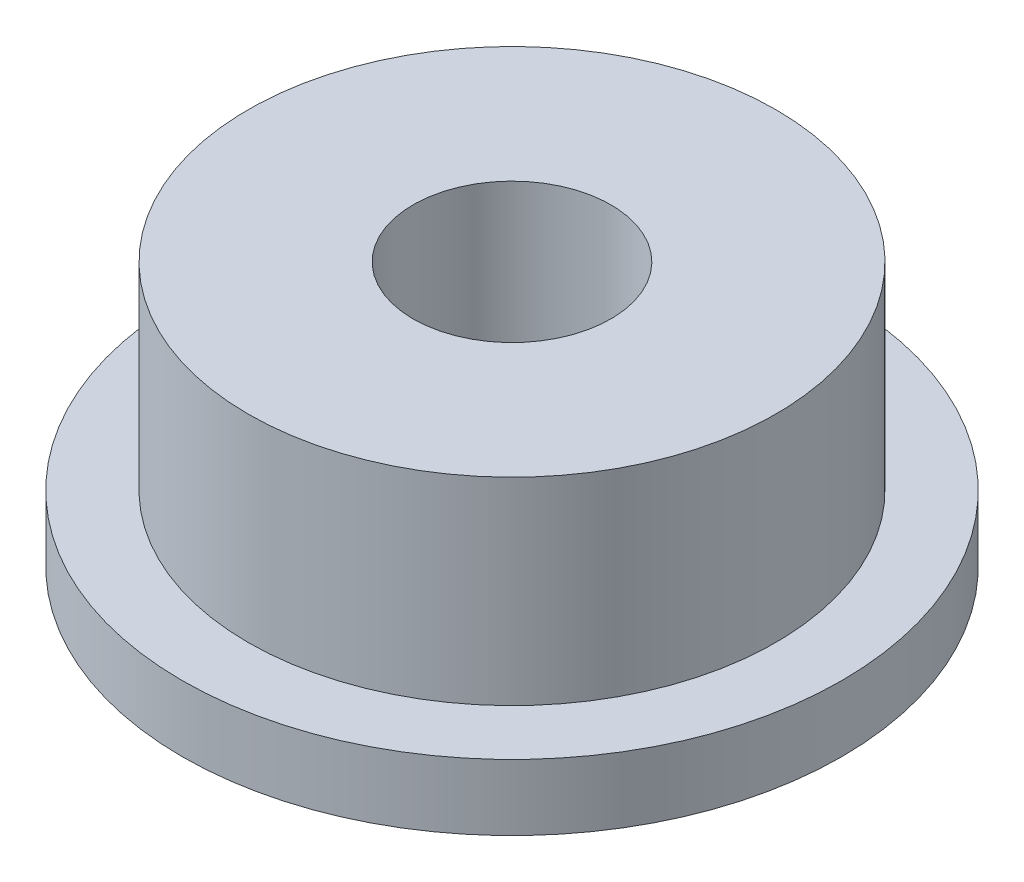
SolidWorks part; units mm, degrees
ref_plane "前视基准面" through (0, 0, 0) normal (0, 0, 1) x (1, 0, 0)
ref_plane "上视基准面" through (0, 0, 0) normal (0, 1, 0) x (1, 0, 0)
ref_plane "右视基准面" through (0, 0, 0) normal (1, 0, 0) x (0, 0, -1)
sketch "草图1" plane through (0, 0, 0) normal (0, 1, 0) x (1, 0, 0)
  circle A0 centre (0, 0) radius 5
  circle A1 centre (0, 0) radius 1.5
  dimension "D1" = 10
  dimension "D2" = 3
extrude "凸台-拉伸1" add sketch "草图1" along normal blind 1
sketch "草图2" plane through (0, 1, 0) normal (0, 1, 0) x (1, 0, 0)
  circle A0 centre (0, 0) radius 4
  circle A1 centre (0, 0) radius 1.5 construction
  circle A2 centre (0, 0) radius 1.5
  dimension "D1" = 8
extrude "凸台-拉伸2" add sketch "草图2" along normal blind 3 contours A0
